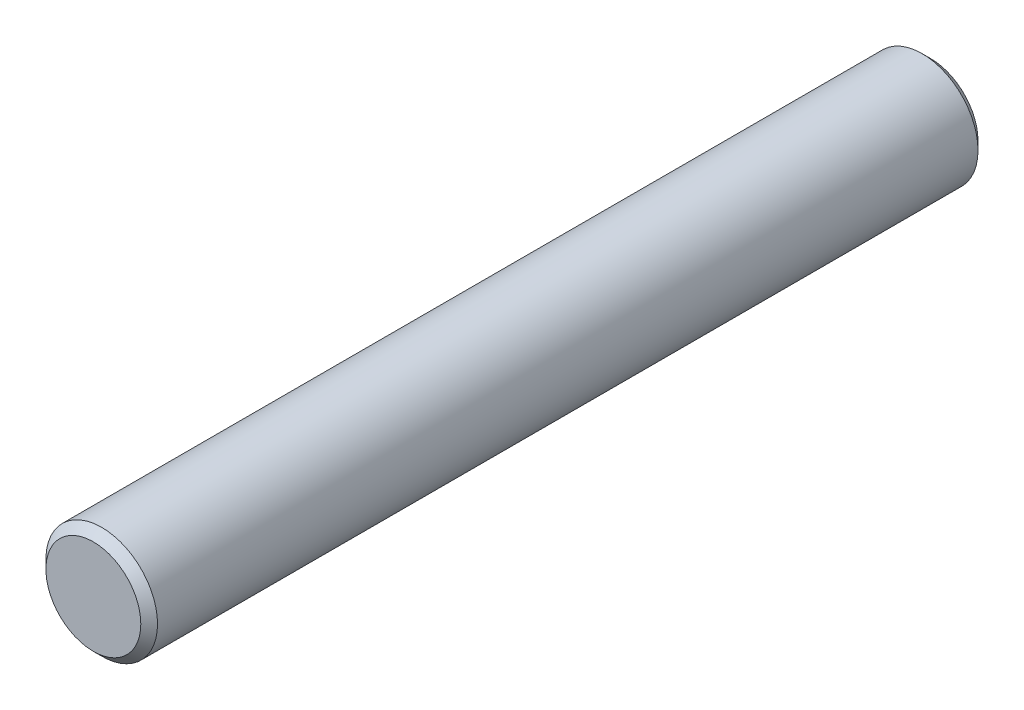
SolidWorks part; units mm, degrees
ref_plane "Front Plane" through (0, 0, 0) normal (0, 0, 1) x (1, 0, 0)
ref_plane "Top Plane" through (0, 0, 0) normal (0, 1, 0) x (1, 0, 0)
ref_plane "Right Plane" through (0, 0, 0) normal (1, 0, 0) x (0, 0, -1)
sketch "Sketch1" plane through (0, 0, 0) normal (0, 0, 1) x (1, 0, 0)
  circle A0 centre (0, 0) radius 2
  dimension "D1" = 4
extrude "Boss-Extrude1" add sketch "Sketch1" along normal blind 30
chamfer "Chamfer1" distance 0.3 angle 45 2 edges at (2, 0, 0) (2, 0, 30)
